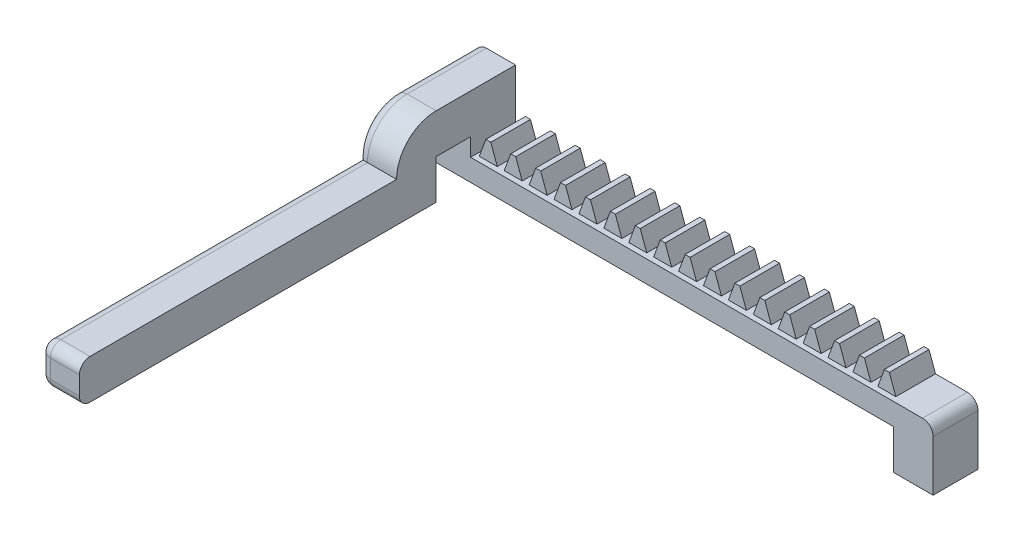
SolidWorks part; units mm, degrees
extrude "Blank" add sketch "BlankSke" against normal blind 20
sketch "BlankSke" plane through (0, 0, 0) normal (0, 0, 1) x (1, 0, 0)
  line L1 (0, 0) -> (80, 0)
  line L2 (0, 0) -> (0, 7.5)
  line L3 (0, 7.5) -> (80, 7.5)
  line L4 (80, 0) -> (80, 7.5)
  dimension "Length" = 80
  dimension "Blank_height" = 7.5
ref_plane "Plane1" through (0, 0, 0) normal (0, 0, 1) x (1, 0, 0)
ref_plane "Plane2" through (0, 0, 0) normal (0, 1, 0) x (1, 0, 0)
ref_plane "Plane3" through (0, 0, 0) normal (1, 0, 0) x (0, 0, -1)
sketch "HoldingSke" plane through (0, 0, 0) normal (0, 1, 0) x (1, 0, 0)
  line L0 (0, 0) -> (0.0928, 0.6602)
  line L1 (-15, 0) -> (100, 0) construction
  line L2 (0, 0) -> (-2.1039, 2.3779)
  line L3 (0, 0) -> (-11.863, 4.5341)
  line L4 (0, 0) -> (8.2133, 2.6687)
  line L5 (0, 0) -> (-23.7986, -8.8762)
  line L6 (0, 0) -> (-10.5278, -7.1032)
  line L9 (-71.009, 38.7566) -> (4.1664, 66.1182)
  line L10 (-76.2, 3.8779) -> (-70.2, 3.8779)
  line L11 (0, 0) -> (-20, 0)
  line L12 (-76.2, 101.6) -> (-76.147, 101.6)
  line L13 (24.9733, 27.94) -> (52.9518, 28.4284)
  line L14 (24.9733, 27.94) -> (24.9743, 27.94)
  line L15 (24.9733, 27.94) -> (100.4006, 29.5858)
  circle A0 centre (0, 0) radius 19.05
  circle A1 centre (0, 0) radius 3
  circle A2 centre (0, 0) radius 12.7
  dimension "MPH" = 6
  dimension "Diameter" = 38.1
  dimension "Num_teeth" = 18
  dimension "Pitch" = 0.6667
  dimension "Show_teeth" = 998
  dimension "Thickness" = 12.7
  dimension "Ap" = 20
  dimension "Pitch_height" = 6
  dimension "Width" = 20
  dimension "Backlash" = 0.053
  dimension "Addendum_fac" = 1
  dimension "Dedendum_fac" = 1.25
  dimension "Clearance_fac" = 0.25
  dimension "Dedendum_add" = 0.001
  dimension "Length" = 80
  dimension "Module" = 1.5
sketch "TooCutSkeIll" plane through (0, 0, 0) normal (0, 0, 1) x (1, 0, 0)
  line L0 (-1.8687, 7.4605) -> (-0.7447, 4.3724)
  line L1 (-0.3914, 4.125) -> (0.3914, 4.125)
  line L2 (0.7447, 4.3724) -> (1.8687, 7.4605)
  line L3 (80, 7.5) -> (0, 7.5) construction
  line L4 (0, 0) -> (0, 64.897) construction
  line L5 (-13.208, 6) -> (12.954, 6) construction
  line L6 (0, 0) -> (80, 0) construction
  line L7 (1.3371, 6) -> (1.3371, 48.7463) construction
  line L8 (-1.3371, 6) -> (-1.3371, 48.7463) construction
  line L9 (1.9251, 7.5) -> (1.9251, 7.5254)
  line L10 (-1.9251, 7.5) -> (-1.9251, 7.5254)
  line L11 (-1.9251, 7.5254) -> (1.9251, 7.5254)
  arc A0 (0.3914, 4.125) -> (0.7447, 4.3724) centre (0.3914, 4.501) ccw
  arc A1 (-0.7447, 4.3724) -> (-0.3914, 4.125) centre (-0.3914, 4.501) ccw
  arc A2 (1.9251, 7.5) -> (1.8687, 7.4605) centre (1.9251, 7.44) ccw
  arc A3 (-1.8687, 7.4605) -> (-1.9251, 7.5) centre (-1.9251, 7.44) ccw
  dimension "Pitch_height" = 6
  dimension "Addendum_plus" = 1.5254
  dimension "Pressure_angle" = 20
  dimension "Gap_width" = 2.6742
  dimension "Dedendum" = 1.875
extrude "ToothCutIll" [suppressed] cut sketch "TooCutSkeIll" against normal through all
sketch "TooCutSkeSim" plane through (0, 0, 0) normal (0, 0, 1) x (1, 0, 0)
  line L0 (0.6547, 4.125) -> (-0.6547, 4.125)
  line L1 (1.8923, 7.5254) -> (0.6547, 4.125)
  line L2 (0, 17.4625) -> (0, 53.467) construction
  line L3 (1.8923, 7.5254) -> (-1.8923, 7.5254)
  line L6 (-1.8923, 7.5254) -> (-0.6547, 4.125)
  line L9 (-1.3371, 6) -> (1.3371, 6) construction
  line L10 (0, 0) -> (80, 0) construction
  line L11 (1.3371, 6) -> (1.3371, 53.467) construction
  line L12 (-1.3371, 6) -> (-1.3371, 53.467) construction
  dimension "Pitch_height" = 6
  dimension "Addendum_plus" = 1.5254
  dimension "Pressure_angle" = 20
  dimension "Gap_width" = 2.6742
  dimension "Dedendum" = 1.875
extrude "ToothCutSim" cut sketch "TooCutSkeSim" against normal through all
pattern_linear "TeethCuts" count 18 spacing 4.7124 along (1, 0, 0) of "ToothCutIll", "ToothCutSim"
sketch "Sketch1" plane through (80, 0, 0) normal (1, 0, 0) x (0, 0, -1)
  line L1 (0, 4.125) -> (20, 4.125)
  line L2 (0, 4.125) -> (0, -7.5)
  line L3 (0, -7.5) -> (20, -7.5)
  line L4 (20, 4.125) -> (20, -7.5)
  line L7 (20, 0) -> (20, 4.125) construction
  dimension "D1" = 11.625
  dimension "D2" = 0
extrude "Boss-Extrude2" add sketch "Sketch1" along normal blind 7.5
sketch "Sketch3" plane through (0, 0, 0) normal (-1, 0, 0) x (0, 0, 1)
  line L1 (-20, 0) -> (0, 0)
  line L2 (-20, 0) -> (-20, 15)
  line L3 (-20, 15) -> (0, 15)
  line L4 (0, 0) -> (0, 15)
  line L5 (0, 4.125) -> (0, 0) construction
  dimension "D1" = 15
  dimension "D2" = 0
extrude "Boss-Extrude3" add sketch "Sketch3" along normal blind 7.5
sketch "Sketch4" plane through (0, 0, 0) normal (0, 0, 1) x (1, 0, 0)
  line L1 (-7.5, 0) -> (0, 0)
  line L2 (-7.5, 0) -> (-7.5, 15)
  line L3 (-7.5, 15) -> (0, 15)
  line L4 (0, 0) -> (0, 15)
extrude "Boss-Extrude4" add sketch "Sketch4" along normal blind 15
sketch "Sketch8" plane through (0, 0, 0) normal (1, 0, 0) x (0, 0, -1)
  line L1 (0, 0) -> (-7.5, 0)
  line L2 (0, 0) -> (0, 7.5)
  line L3 (0, 7.5) -> (-7.5, 7.5)
  line L4 (-7.5, 0) -> (-7.5, 7.5)
  dimension "D1" = 7.5
  dimension "D2" = 7.5
extrude "Cut-Extrude1" cut sketch "Sketch8" against normal blind 15
sketch "Sketch9" plane through (-7.5, 0, 0) normal (-1, 0, 0) x (0, 0, 1)
  line L0 (7.5, 15) -> (15, 7.5)
  line L1 (15, 15) -> (-20, 15) construction
  line L2 (15, 15) -> (15, 0) construction
  line L3 (7.5, 15) -> (15, 15)
  line L4 (15, 15) -> (15, 7.5)
  dimension "D1" = 7.5
  dimension "D2" = 7.5
extrude "Cut-Extrude2" cut sketch "Sketch9" against normal blind 15
sketch "Sketch10" plane through (0, 0, 0) normal (0, -1, 0) x (1, 0, 0)
  line L1 (-7.5, 7.5) -> (0, 7.5)
  line L2 (-7.5, 7.5) -> (-7.5, 15)
  line L3 (-7.5, 15) -> (0, 15)
  line L4 (0, 7.5) -> (0, 15)
extrude "Boss-Extrude5" add sketch "Sketch10" along normal blind 7.5
sketch "Sketch11" plane through (0, 0, 15) normal (0, 0, 1) x (1, 0, 0)
  line L1 (-7.5, 7.5) -> (0, 7.5)
  line L2 (-7.5, 7.5) -> (-7.5, -7.5)
  line L3 (-7.5, -7.5) -> (0, -7.5)
  line L4 (0, 7.5) -> (0, -7.5)
  line L5 (-7.5, -7.5) -> (0, -7.5)
  line L6 (-7.5, -7.5) -> (-7.5, 7.5)
  line L7 (-7.5, 7.5) -> (0, 7.5)
  line L8 (0, -7.5) -> (0, 7.5)
  line M1 (0, -7.5) -> (0, 7.5)
  line M2 (0, 7.5) -> (-7.5, 7.5)
  line M3 (-7.5, 7.5) -> (-7.5, -7.5)
  line M4 (-7.5, -7.5) -> (0, -7.5)
extrude "Boss-Extrude7" add sketch "Sketch11" along normal blind 60 contours M4 M1 M2 M3
sketch "Sketch12" plane through (0, 4.125, 0) normal (0, 1, 0) x (1, 0, 0)
  line L0 (87.5, 20) -> (87.5, 0) construction
  line L1 (-7.5, 20) -> (87.5, 20)
  line L2 (-7.5, 20) -> (-7.5, 10)
  line L3 (-7.5, 10) -> (87.5, 10)
  line L4 (87.5, 20) -> (87.5, 10)
extrude "Cut-Extrude4" cut sketch "Sketch12" along normal through all both and the other way through all
sketch "Sketch14" plane through (0, 15, 0) normal (0, 1, 0) x (1, 0, 0)
  line L0 (87.5, 10) -> (87.5, 0) construction
  line L1 (-7.5, 10) -> (87.5, 10)
  line L2 (-7.5, 10) -> (-7.5, 7.5)
  line L3 (-7.5, 7.5) -> (87.5, 7.5)
  line L4 (87.5, 10) -> (87.5, 7.5)
  dimension "D1" = 2.5
extrude "Cut-Extrude5" cut sketch "Sketch14" against normal blind 100
sketch "Sketch15" plane through (-7.5, 0, 0) normal (-1, 0, 0) x (0, 0, 1)
  line L0 (75, 7.5) -> (75, -7.5) construction
  line L1 (7.5, -7.5) -> (75, -7.5)
  line L2 (7.5, -7.5) -> (7.5, 0)
  line L3 (7.5, 0) -> (75, 0)
  line L4 (75, -7.5) -> (75, 0)
extrude "Cut-Extrude6" cut sketch "Sketch15" against normal through all
sketch "Sketch16" plane through (-7.5, 0, 0) normal (-1, 0, 0) x (0, 0, 1)
  line L0 (7.5, 7.5) -> (7.5, 15)
  line L1 (15, 7.5) -> (7.5, 7.5)
  arc A0 (7.5, 15) -> (15, 7.5) centre (7.5, 7.5) cw
extrude "Boss-Extrude8" add sketch "Sketch16" against normal up to vertex
sketch "Sketch19" plane through (0, 0, 0) normal (0, 0, 1) x (1, 0, 0)
  line L0 (-7.5, 0) -> (-7.5, 7.5)
  line L1 (-7.5, 7.5) -> (0, 7.5)
  line L2 (0, 7.5) -> (0, 4.125)
  line L3 (0, 4.125) -> (87.5, 4.125)
  line L4 (87.5, 4.125) -> (87.5, -7.5)
  line L5 (87.5, -7.5) -> (80, -7.5)
  line L6 (80, -7.5) -> (80, 0)
  line L7 (80, 0) -> (-7.5, 0)
extrude "Boss-Extrude9" add sketch "Sketch19" along normal blind 1
fillet "Fillet1" radius 2 3 edges at (-7.5, 12.8033, 12.8033) (-7.5, 7.5, 45) (-7.5, 15, 0)
fillet "Fillet2" radius 2 5 edges at (-2.75, 7.5, 75) (-6.9142, 6.9142, 75) (-3.75, 0, 75) (-7.5, 0, 41.25) (-7.5, 2.75, 75)
fillet "Fillet3" radius 2 1 edges at (87.5, 4.125, -3.25)
equation "' \"Module@HoldingSke\" = 6.35"
equation "' \"Num_teeth@HoldingSke\" = 12"
equation "' \"Ap@HoldingSke\" =  20"
equation "' \"Ap@HoldingSke\" = 20"
equation "' \"Width@HoldingSke\" = 0.25 * 25.4"
equation "' \"Show_teeth@HoldingSke\" = 500"
equation "' \"Backlash@HoldingSke\" = 0.009 * 25.4"
equation "' \"Addendum_fac@HoldingSke\" = 1.0"
equation "' \"Dedendum_fac@HoldingSke\" = 1.25"
equation "' \"Dedendum_add@HoldingSke\" = 0.00005 * 25.4"
equation "' \"Clearance_fac@HoldingSke\" = 0.25"
equation "' \"Pitch_height@HoldingSke\" = 1 * 25.4"
equation "' \"Length@HoldingSke\" = 4.71 * 25.4"
equation "\"Pitch@HoldingSke\" = 1 / \"Module@HoldingSke\""
equation "\"MPH@HoldingSke\" = \"Dedendum_fac@HoldingSke\" / \"Pitch@HoldingSke\" + 2 * \"Dedendum_add@HoldingSke\" + 0.002 * 25.4"
equation "\"MPH@HoldingSke\" = ((sgn( \"MPH@HoldingSke\" - \"Pitch_height@HoldingSke\")+1)*( \"MPH@HoldingSke\" - \"Pitch_height@HoldingSke\"))/2 + \"Pitch_height@HoldingSke\""
equation "\"Blank_height@BlankSke\" = \"Pitch_height@HoldingSke\" + \"Addendum_fac@HoldingSke\"  / \"Pitch@HoldingSke\" "
equation "\"Length@BlankSke\" =  \"Length@HoldingSke\""
equation "\"Face_width@Blank\" = \"Width@HoldingSke\""
equation "\"Pressure_angle@TooCutSkeIll\" = \"Ap@HoldingSke\""
equation "\"Addendum_plus@TooCutSkeIll\" =  \"Addendum_fac@HoldingSke\"  / \"Pitch@HoldingSke\" + 0.001 *25.4"
equation "\"Dedendum@TooCutSkeIll\" = \"Dedendum_fac@HoldingSke\"  / \"Pitch@HoldingSke\""
equation "\"Pitch_height@TooCutSkeIll\" =  \"MPH@HoldingSke\""
equation "\"Gap_width@TooCutSkeIll\" = 3.14159265 / 2 / \"Pitch@HoldingSke\" + 6 * \"Backlash@HoldingSke\""
equation "\"Pressure_angle@TooCutSkeSim\" = \"Ap@HoldingSke\""
equation "\"Addendum_plus@TooCutSkeSim\" =  \"Addendum_fac@HoldingSke\"  / \"Pitch@HoldingSke\" + 0.001 * 25.4"
equation "\"Dedendum@TooCutSkeSim\" = \"Dedendum_fac@HoldingSke\"  / \"Pitch@HoldingSke\""
equation "\"Pitch_height@TooCutSkeSim\" =  \"MPH@HoldingSke\""
equation "\"Gap_width@TooCutSkeSim\" = 3.14159265 / 2 / \"Pitch@HoldingSke\" + 6 * \"Backlash@HoldingSke\""
equation "\"Root_fillet@TooCutSkeIll\" = \"Clearance_fac@HoldingSke\" / \"Pitch@HoldingSke\" + \"Dedendum_add@HoldingSke\""
equation "\"Break_rad@TooCutSkeIll\" = 0.02 / \"Pitch@HoldingSke\" * 2"
equation "\"Linear_pitch@TeethCuts\" = 3.14159265 / \"Pitch@HoldingSke\""
equation "\"Num_teeth@HoldingSke\" = int( ( \"Length@HoldingSke\" + 0 ) / (3.14159265 / \"Pitch@HoldingSke\")) + 0.9999  + 1"
equation " \"Num_teeth@TeethCuts\" = int( \"Show_teeth@HoldingSke\" ) + 1"
equation " \"Num_teeth@TeethCuts\" = ((sgn( \"Num_teeth@TeethCuts\" - \"Num_teeth@HoldingSke\" )-1)*( \"Num_teeth@TeethCuts\" - \"Num_teeth@HoldingSke\" ))/-2+ \"Num_teeth@HoldingSke\""
equation " \"Num_teeth@TeethCuts\" = ((sgn( \"Num_teeth@TeethCuts\" - 2.0)+1)*( \"Num_teeth@TeethCuts\" - 2.0))/2 +2.0"
